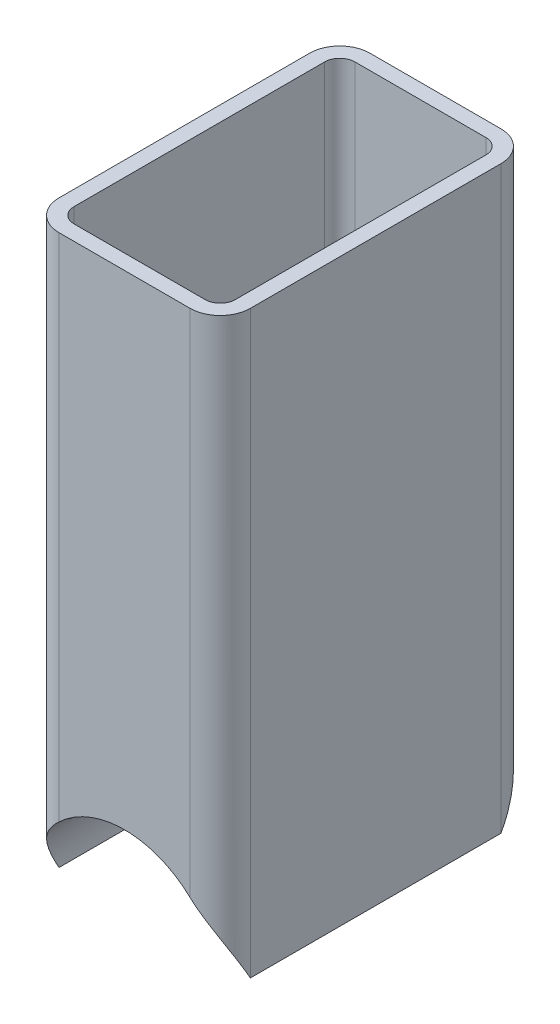
SolidWorks part; units mm, degrees
material "1.0037 (S235JR)"
ref_plane "E_Rechts" through (0, 0, 0) normal (0, 0, 1) x (1, 0, 0)
ref_plane "E_Vorne" through (0, 0, 0) normal (0, 1, 0) x (1, 0, 0)
ref_plane "E_Oben" through (0, 0, 0) normal (1, 0, 0) x (0, 0, -1)
sketch "Skizze1" plane through (0, 0, 0) normal (0, 1, 0) x (1, 0, 0)
  line L0 (-27.4, -58.7) -> (27.4, -58.7)
  line L1 (-33.7, -52.4) -> (-33.7, 52.4)
  line L2 (27.4, 58.7) -> (-27.4, 58.7)
  line L3 (33.7, 52.4) -> (33.7, -52.4)
  line L4 (-27.4, -65) -> (27.4, -65)
  line L5 (-40, -52.4) -> (-40, 52.4)
  line L6 (27.4, 65) -> (-27.4, 65)
  line L7 (40, 52.4) -> (40, -52.4)
  line L8 (-55, 0) -> (55, 0) construction
  line L9 (0, -55) -> (0, 55) construction
  arc A0 (40, 52.4) -> (27.4, 65) centre (27.4, 52.4) ccw
  arc A1 (27.4, -65) -> (40, -52.4) centre (27.4, -52.4) ccw
  arc A2 (-40, -52.4) -> (-27.4, -65) centre (-27.4, -52.4) ccw
  arc A3 (-27.4, 65) -> (-40, 52.4) centre (-27.4, 52.4) ccw
  arc A4 (-27.4, 58.7) -> (-33.7, 52.4) centre (-27.4, 52.4) ccw
  arc A5 (33.7, 52.4) -> (27.4, 58.7) centre (27.4, 52.4) ccw
  arc A6 (27.4, -58.7) -> (33.7, -52.4) centre (27.4, -52.4) ccw
  arc A7 (-33.7, -52.4) -> (-27.4, -58.7) centre (-27.4, -52.4) ccw
  dimension "D1" = 12.6
  dimension "D2" = 6.3
  dimension "D3" = 130
  dimension "D4" = 80
  dimension "D5" = 65
  dimension "D6" = 65
  dimension "D7" = 40
  dimension "D8" = 40
extrude "Aufsatz-Linear austragen1" add sketch "Skizze1" along normal blind 242.5
sketch "Skizze2" plane through (0, 0, 0) normal (0, 0, 1) x (1, 0, 0)
  circle A0 centre (0, 0) radius 40
extrude "Schnitt-Linear austragen1" cut sketch "Skizze2" against normal through all both and the other way through all
